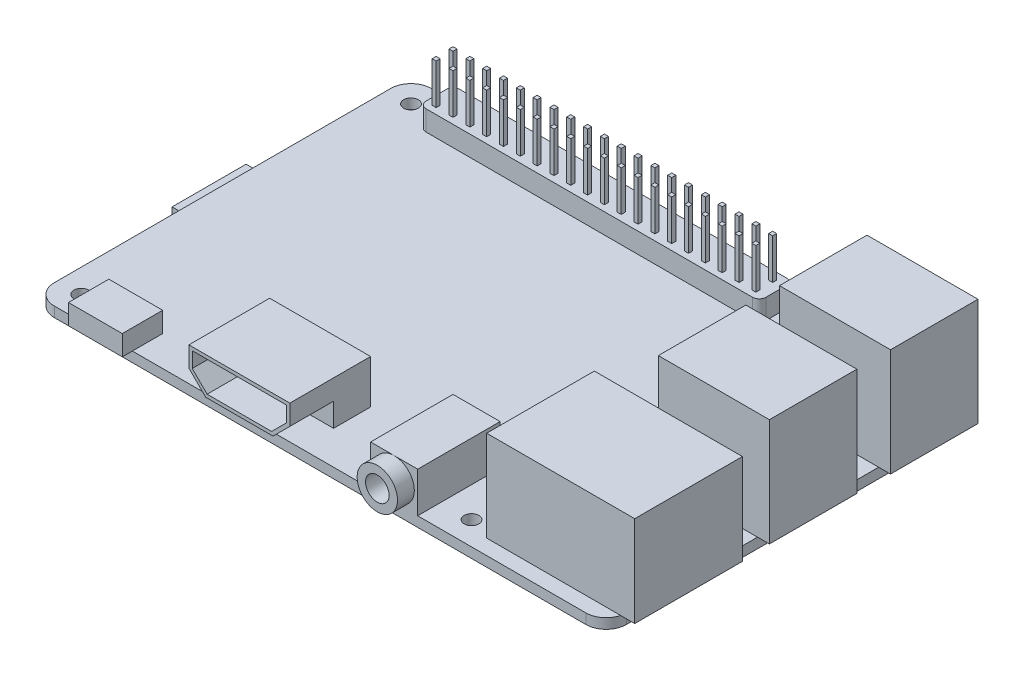
SolidWorks part; units mm, degrees
ref_plane "Front" through (0, 0, 0) normal (0, 0, 1) x (1, 0, 0)
ref_plane "Top" through (0, 0, 0) normal (0, 1, 0) x (1, 0, 0)
ref_plane "Right" through (0, 0, 0) normal (1, 0, 0) x (0, 0, -1)
sketch "Sketch1" plane through (0, 0, 0) normal (0, 1, 0) x (1, 0, 0)
  line L0 (-42.5, 28) -> (42.5, -28) construction
  line L1 (-42.5, 28) -> (42.5, 28)
  line L2 (-42.5, 28) -> (-42.5, -28)
  line L3 (-42.5, -28) -> (42.5, -28)
  line L4 (42.5, 28) -> (42.5, -28)
  line L5 (-42.5, -28) -> (42.5, 28) construction
  circle A0 centre (-39, 24.5) radius 2.6471
  circle A1 centre (-39, 24.5) radius 1.0947
  circle A2 centre (19, 24.5) radius 1.0947
  circle A3 centre (19, 24.5) radius 2.6471
  circle A4 centre (19, -24.5) radius 1.0947
  circle A5 centre (19, -24.5) radius 2.6471
  circle A6 centre (-39, -24.5) radius 1.0947
  circle A7 centre (-39, -24.5) radius 2.6471
  dimension "D1" = 85
  dimension "D2" = 56
  dimension "D3" = 3.5
  dimension "D4" = 3.5
  dimension "D5" = 2
  dimension "D6" = 2
extrude "Boss-Extrude1" add sketch "Sketch1" along normal blind 1.5 contours A0 A1 | A7 A6 | A5 A4 | L4 L1 L2 L3 A7 A5 A3 A0 | A3 A2
fillet "Fillet1" radius 3 4 edges at (42.5, 0.75, -28) (42.5, 0.75, 28) (-42.5, 0.75, 28) (-42.5, 0.75, -28)
sketch "Sketch2" plane through (0, 1.5, 0) normal (0, 1, 0) x (1, 0, 0)
  line L0 (-10.5, -29.5) -> (-10.5, -17.5) construction
  line L1 (-18, -17.5) -> (-3, -17.5)
  line L2 (-18, -17.5) -> (-18, -29.5)
  line L3 (-18, -29.5) -> (-3, -29.5)
  line L4 (-3, -17.5) -> (-3, -29.5)
  line L5 (-42.5, 25) -> (-42.5, -25) construction
  line L7 (-39.5, -28) -> (39.5, -28) construction
  dimension "D1" = 32
  dimension "D2" = 15
  dimension "D3" = 12
  dimension "D4" = 1.5
extrude "Boss-Extrude2" add sketch "Sketch2" along normal blind 6.5
sketch "Sketch3" plane through (0, 0, 29.5) normal (0, 0, 1) x (1, 0, 0)
  line L0 (-10.5, 7.5) -> (-3.5, 7.5)
  line L1 (-3.5, 7.5) -> (-3.5, 5.2071)
  line L2 (-3.5, 5.2071) -> (-5.7071, 3)
  line L3 (-5.7071, 3) -> (-10.5, 3)
  line L6 (-10.5, 8) -> (-3, 8)
  line L7 (-10.5, 8) -> (-10.5, 1.5) construction
  line L8 (-18, 8) -> (-3, 8) construction
  line L9 (-18, 1.5) -> (-3, 1.5) construction
  line L10 (-3, 8) -> (-3, 5)
  line L11 (-3, 5) -> (-5.5, 2.5)
  line L12 (-5.5, 2.5) -> (-10.5, 2.5)
  line L14 (-3, 8) -> (-3, 1.5) construction
  line L15 (-15.2929, 3) -> (-10.5, 3)
  line L16 (-15.5, 2.5) -> (-10.5, 2.5)
  line L17 (-18, 5) -> (-15.5, 2.5)
  line L18 (-17.5, 5.2071) -> (-15.2929, 3)
  line L19 (-17.5, 7.5) -> (-17.5, 5.2071)
  line L20 (-18, 8) -> (-18, 5)
  line L21 (-10.5, 8) -> (-18, 8)
  line L22 (-10.5, 7.5) -> (-17.5, 7.5)
  line M8 (-18, 1.5) -> (-3, 1.5)
  line M9 (-3, 1.5) -> (-3, 8)
  line M11 (-18, 8) -> (-18, 1.5)
  dimension "D1" = 7
  dimension "D3" = 1
  dimension "D4" = 5.5
  dimension "D5" = 2.5
  dimension "D6" = 45
  dimension "D2" = 0.5
extrude "Cut-Extrude1" cut sketch "Sketch3" against normal blind 6.5 contours L7 L22 L19 L18 L15 | L0 L7 L3 L2 L1 | L7 L16 L17 M11 M8 | L12 L7 L11 M8 M9
sketch "Sketch4" plane through (0, 1.5, 0) normal (0, 1, 0) x (1, 0, 0)
  line L0 (27.7652, 19) -> (44.2652, 19) construction
  line L1 (27.7652, 25.5) -> (44.2652, 25.5)
  line L2 (27.7652, 25.5) -> (27.7652, 12.5)
  line L3 (27.7652, 12.5) -> (44.2652, 12.5)
  line L4 (44.2652, 25.5) -> (44.2652, 12.5)
  line L5 (-39.5, -28) -> (39.5, -28) construction
  line L6 (27.7652, 7.5) -> (27.7652, -5.5)
  line L7 (27.7652, 7.5) -> (44.2652, 7.5)
  line L8 (44.2652, 7.5) -> (44.2652, -5.5)
  line L9 (27.7652, -5.5) -> (44.2652, -5.5)
  dimension "D1" = 47
  dimension "D2" = 16.5
  dimension "D3" = 13
  dimension "D4" = 2
extrude "Boss-Extrude3" add sketch "Sketch4" along normal blind 16
sketch "Sketch5" plane through (0, 1.5, 0) normal (0, 1, 0) x (1, 0, 0)
  line L0 (22.5, -17.75) -> (44.5, -17.75) construction
  line L1 (22.5, -9.75) -> (44.5, -9.75)
  line L2 (22.5, -9.75) -> (22.5, -25.75)
  line L3 (22.5, -25.75) -> (44.5, -25.75)
  line L4 (44.5, -9.75) -> (44.5, -25.75)
  line L5 (-39.5, -28) -> (39.5, -28) construction
  line L6 (42.5, -5.5) -> (42.5, -25) construction
  dimension "D1" = 10.25
  dimension "D2" = 22
  dimension "D3" = 16
  dimension "D4" = 2
extrude "Boss-Extrude4" add sketch "Sketch5" along normal blind 13.5
sketch "Sketch6" plane through (0, 1.5, 0) normal (0, 1, 0) x (1, 0, 0)
  line L0 (11, -15.75) -> (11, -30.5) construction
  line L1 (7.5, -15.75) -> (14.5, -15.75)
  line L2 (7.5, -15.75) -> (7.5, -30.5)
  line L3 (7.5, -30.5) -> (14.5, -30.5)
  line L4 (14.5, -15.75) -> (14.5, -30.5)
  line L5 (-42.5, 25) -> (-42.5, -25) construction
  line L6 (-39.5, -28) -> (39.5, -28) construction
  dimension "D1" = 14.75
  dimension "D2" = 7
  dimension "D3" = 53.5
  dimension "D4" = 2.5
extrude "Boss-Extrude5" add sketch "Sketch6" along normal blind 6
sketch "Sketch7" plane through (0, 0, 30.5) normal (0, 0, 1) x (1, 0, 0)
  line L0 (14.5, 4.5) -> (7.5, 4.5) construction
  line L1 (14.5, 7.5) -> (14.5, 1.5) construction
  line L2 (7.5, 7.5) -> (7.5, 1.5) construction
  circle A0 centre (11, 4.5) radius 3
  circle A1 centre (11, 4.5) radius 1.75
  line M3 (7.5, 1.5) -> (14.5, 1.5)
  line M4 (14.5, 1.5) -> (14.5, 7.5)
  line M5 (14.5, 7.5) -> (7.5, 7.5)
  line M6 (7.5, 7.5) -> (7.5, 1.5)
  dimension "D1" = 6
  dimension "D2" = 3.5
extrude "Cut-Extrude2" cut sketch "Sketch7" against normal blind 2.5 contours L0 A0 M5 M6 | L0 A0 M4 M5 | L0 A0 M4 M3 | A0 L0 M6 M3 | A1
sketch "Sketch8" plane through (0, 1.5, 0) normal (0, 1, 0) x (1, 0, 0)
  line L0 (-31.9, -29.5) -> (-31.9, -23.5) construction
  line L1 (-35.9, -23.5) -> (-27.9, -23.5)
  line L2 (-35.9, -23.5) -> (-35.9, -29.5)
  line L3 (-35.9, -29.5) -> (-27.9, -29.5)
  line L4 (-27.9, -23.5) -> (-27.9, -29.5)
  line L5 (-42.5, 25) -> (-42.5, -25) construction
  line L6 (-39.5, -28) -> (7.5, -28) construction
  dimension "D1" = 10.6
  dimension "D2" = 6
  dimension "D3" = 8
  dimension "D4" = 1.5
extrude "Boss-Extrude6" add sketch "Sketch8" along normal blind 3
sketch "Sketch9" plane through (0, 1.5, 0) normal (0, 1, 0) x (1, 0, 0)
  line L0 (-10, 27) -> (-10, 22) construction
  line L1 (-35.25, 27) -> (15.25, 27)
  line L2 (-35.25, 27) -> (-35.25, 22)
  line L3 (-35.25, 22) -> (15.25, 22)
  line L4 (15.25, 27) -> (15.25, 22)
  line L6 (-39, 24.5) -> (-10, 24.5) construction
  dimension "D1" = 29
  dimension "D2" = 5
  dimension "D3" = 50.5
extrude "Boss-Extrude7" add sketch "Sketch9" along normal blind 3
fillet "Fillet2" radius 1 4 edges at (-35.25, 3, -27) (15.25, 3, -27) (15.25, 3, -22) (-35.25, 3, -22)
sketch "Sketch10" plane through (0, 4.5, 0) normal (0, 1, 0) x (1, 0, 0)
  line L0 (-33.65, 25.7) -> (-35.25, 25.7) construction
  line L1 (-34.25, 25.4) -> (-33.65, 25.4)
  line L2 (-34.25, 25.4) -> (-34.25, 26)
  line L3 (-34.25, 26) -> (-33.65, 26)
  line L4 (-33.65, 25.4) -> (-33.65, 26)
  line L7 (-35.25, 26) -> (-35.25, 23) construction
  line L8 (-33.95, 26) -> (-33.95, 27) construction
  line L9 (14.25, 27) -> (-34.25, 27) construction
  line L10 (-31.75, 25.4) -> (-31.75, 26)
  line L11 (-31.75, 25.4) -> (-31.15, 25.4)
  line L12 (-31.15, 25.4) -> (-31.15, 26)
  line L13 (-31.75, 26) -> (-31.15, 26)
  line L14 (-29.25, 25.4) -> (-29.25, 26)
  line L15 (-29.25, 25.4) -> (-28.65, 25.4)
  line L16 (-28.65, 25.4) -> (-28.65, 26)
  line L17 (-29.25, 26) -> (-28.65, 26)
  line L18 (-26.75, 25.4) -> (-26.75, 26)
  line L19 (-26.75, 25.4) -> (-26.15, 25.4)
  line L20 (-26.15, 25.4) -> (-26.15, 26)
  line L21 (-26.75, 26) -> (-26.15, 26)
  line L22 (-24.25, 25.4) -> (-24.25, 26)
  line L23 (-24.25, 25.4) -> (-23.65, 25.4)
  line L24 (-23.65, 25.4) -> (-23.65, 26)
  line L25 (-24.25, 26) -> (-23.65, 26)
  line L26 (-21.75, 25.4) -> (-21.75, 26)
  line L27 (-21.75, 25.4) -> (-21.15, 25.4)
  line L28 (-21.15, 25.4) -> (-21.15, 26)
  line L29 (-21.75, 26) -> (-21.15, 26)
  line L30 (-19.25, 25.4) -> (-19.25, 26)
  line L31 (-19.25, 25.4) -> (-18.65, 25.4)
  line L32 (-18.65, 25.4) -> (-18.65, 26)
  line L33 (-19.25, 26) -> (-18.65, 26)
  line L34 (-16.75, 25.4) -> (-16.75, 26)
  line L35 (-16.75, 25.4) -> (-16.15, 25.4)
  line L36 (-16.15, 25.4) -> (-16.15, 26)
  line L37 (-16.75, 26) -> (-16.15, 26)
  line L38 (-14.25, 25.4) -> (-14.25, 26)
  line L39 (-14.25, 25.4) -> (-13.65, 25.4)
  line L40 (-13.65, 25.4) -> (-13.65, 26)
  line L41 (-14.25, 26) -> (-13.65, 26)
  line L42 (-11.75, 25.4) -> (-11.75, 26)
  line L43 (-11.75, 25.4) -> (-11.15, 25.4)
  line L44 (-11.15, 25.4) -> (-11.15, 26)
  line L45 (-11.75, 26) -> (-11.15, 26)
  line L46 (-9.25, 25.4) -> (-9.25, 26)
  line L47 (-9.25, 25.4) -> (-8.65, 25.4)
  line L48 (-8.65, 25.4) -> (-8.65, 26)
  line L49 (-9.25, 26) -> (-8.65, 26)
  line L50 (-6.75, 25.4) -> (-6.75, 26)
  line L51 (-6.75, 25.4) -> (-6.15, 25.4)
  line L52 (-6.15, 25.4) -> (-6.15, 26)
  line L53 (-6.75, 26) -> (-6.15, 26)
  line L54 (-4.25, 25.4) -> (-4.25, 26)
  line L55 (-4.25, 25.4) -> (-3.65, 25.4)
  line L56 (-3.65, 25.4) -> (-3.65, 26)
  line L57 (-4.25, 26) -> (-3.65, 26)
  line L58 (-1.75, 25.4) -> (-1.75, 26)
  line L59 (-1.75, 25.4) -> (-1.15, 25.4)
  line L60 (-1.15, 25.4) -> (-1.15, 26)
  line L61 (-1.75, 26) -> (-1.15, 26)
  line L62 (0.75, 25.4) -> (0.75, 26)
  line L63 (0.75, 25.4) -> (1.35, 25.4)
  line L64 (1.35, 25.4) -> (1.35, 26)
  line L65 (0.75, 26) -> (1.35, 26)
  line L66 (3.25, 25.4) -> (3.25, 26)
  line L67 (3.25, 25.4) -> (3.85, 25.4)
  line L68 (3.85, 25.4) -> (3.85, 26)
  line L69 (3.25, 26) -> (3.85, 26)
  line L70 (5.75, 25.4) -> (5.75, 26)
  line L71 (5.75, 25.4) -> (6.35, 25.4)
  line L72 (6.35, 25.4) -> (6.35, 26)
  line L73 (5.75, 26) -> (6.35, 26)
  line L74 (8.25, 25.4) -> (8.25, 26)
  line L75 (8.25, 25.4) -> (8.85, 25.4)
  line L76 (8.85, 25.4) -> (8.85, 26)
  line L77 (8.25, 26) -> (8.85, 26)
  line L78 (10.75, 25.4) -> (10.75, 26)
  line L79 (10.75, 25.4) -> (11.35, 25.4)
  line L80 (11.35, 25.4) -> (11.35, 26)
  line L81 (10.75, 26) -> (11.35, 26)
  line L82 (13.25, 25.4) -> (13.25, 26)
  line L83 (13.25, 25.4) -> (13.85, 25.4)
  line L84 (13.85, 25.4) -> (13.85, 26)
  line L85 (13.25, 26) -> (13.85, 26)
  line L86 (-31.75, 22.9) -> (-31.75, 23.5)
  line L87 (-31.75, 22.9) -> (-31.15, 22.9)
  line L88 (-31.15, 22.9) -> (-31.15, 23.5)
  line L89 (-31.75, 23.5) -> (-31.15, 23.5)
  line L90 (-29.25, 22.9) -> (-29.25, 23.5)
  line L91 (-29.25, 22.9) -> (-28.65, 22.9)
  line L92 (-28.65, 22.9) -> (-28.65, 23.5)
  line L93 (-29.25, 23.5) -> (-28.65, 23.5)
  line L94 (-26.75, 22.9) -> (-26.75, 23.5)
  line L95 (-26.75, 22.9) -> (-26.15, 22.9)
  line L96 (-26.15, 22.9) -> (-26.15, 23.5)
  line L97 (-26.75, 23.5) -> (-26.15, 23.5)
  line L98 (-24.25, 22.9) -> (-24.25, 23.5)
  line L99 (-24.25, 22.9) -> (-23.65, 22.9)
  line L100 (-23.65, 22.9) -> (-23.65, 23.5)
  line L101 (-24.25, 23.5) -> (-23.65, 23.5)
  line L102 (-21.75, 22.9) -> (-21.75, 23.5)
  line L103 (-21.75, 22.9) -> (-21.15, 22.9)
  line L104 (-21.15, 22.9) -> (-21.15, 23.5)
  line L105 (-21.75, 23.5) -> (-21.15, 23.5)
  line L106 (-19.25, 22.9) -> (-19.25, 23.5)
  line L107 (-19.25, 22.9) -> (-18.65, 22.9)
  line L108 (-18.65, 22.9) -> (-18.65, 23.5)
  line L109 (-19.25, 23.5) -> (-18.65, 23.5)
  line L110 (-16.75, 22.9) -> (-16.75, 23.5)
  line L111 (-16.75, 22.9) -> (-16.15, 22.9)
  line L112 (-16.15, 22.9) -> (-16.15, 23.5)
  line L113 (-16.75, 23.5) -> (-16.15, 23.5)
  line L114 (-14.25, 22.9) -> (-14.25, 23.5)
  line L115 (-14.25, 22.9) -> (-13.65, 22.9)
  line L116 (-13.65, 22.9) -> (-13.65, 23.5)
  line L117 (-14.25, 23.5) -> (-13.65, 23.5)
  line L118 (-11.75, 22.9) -> (-11.75, 23.5)
  line L119 (-11.75, 22.9) -> (-11.15, 22.9)
  line L120 (-11.15, 22.9) -> (-11.15, 23.5)
  line L121 (-11.75, 23.5) -> (-11.15, 23.5)
  line L122 (-9.25, 22.9) -> (-9.25, 23.5)
  line L123 (-9.25, 22.9) -> (-8.65, 22.9)
  line L124 (-8.65, 22.9) -> (-8.65, 23.5)
  line L125 (-9.25, 23.5) -> (-8.65, 23.5)
  line L126 (-6.75, 22.9) -> (-6.75, 23.5)
  line L127 (-6.75, 22.9) -> (-6.15, 22.9)
  line L128 (-6.15, 22.9) -> (-6.15, 23.5)
  line L129 (-6.75, 23.5) -> (-6.15, 23.5)
  line L130 (-4.25, 22.9) -> (-4.25, 23.5)
  line L131 (-4.25, 22.9) -> (-3.65, 22.9)
  line L132 (-3.65, 22.9) -> (-3.65, 23.5)
  line L133 (-4.25, 23.5) -> (-3.65, 23.5)
  line L134 (-1.75, 22.9) -> (-1.75, 23.5)
  line L135 (-1.75, 22.9) -> (-1.15, 22.9)
  line L136 (-1.15, 22.9) -> (-1.15, 23.5)
  line L137 (-1.75, 23.5) -> (-1.15, 23.5)
  line L138 (0.75, 22.9) -> (0.75, 23.5)
  line L139 (0.75, 22.9) -> (1.35, 22.9)
  line L140 (1.35, 22.9) -> (1.35, 23.5)
  line L141 (0.75, 23.5) -> (1.35, 23.5)
  line L142 (3.25, 22.9) -> (3.25, 23.5)
  line L143 (3.25, 22.9) -> (3.85, 22.9)
  line L144 (3.85, 22.9) -> (3.85, 23.5)
  line L145 (3.25, 23.5) -> (3.85, 23.5)
  line L146 (5.75, 22.9) -> (5.75, 23.5)
  line L147 (5.75, 22.9) -> (6.35, 22.9)
  line L148 (6.35, 22.9) -> (6.35, 23.5)
  line L149 (5.75, 23.5) -> (6.35, 23.5)
  line L150 (8.25, 22.9) -> (8.25, 23.5)
  line L151 (8.25, 22.9) -> (8.85, 22.9)
  line L152 (8.85, 22.9) -> (8.85, 23.5)
  line L153 (8.25, 23.5) -> (8.85, 23.5)
  line L154 (10.75, 22.9) -> (10.75, 23.5)
  line L155 (10.75, 22.9) -> (11.35, 22.9)
  line L156 (11.35, 22.9) -> (11.35, 23.5)
  line L157 (10.75, 23.5) -> (11.35, 23.5)
  line L158 (13.25, 22.9) -> (13.25, 23.5)
  line L159 (13.25, 22.9) -> (13.85, 22.9)
  line L160 (13.85, 22.9) -> (13.85, 23.5)
  line L161 (13.25, 23.5) -> (13.85, 23.5)
  line L162 (-34.25, 22.9) -> (-34.25, 23.5)
  line L163 (-34.25, 22.9) -> (-33.65, 22.9)
  line L164 (-33.65, 22.9) -> (-33.65, 23.5)
  line L165 (-34.25, 23.5) -> (-33.65, 23.5)
  dimension "D1" = 1
  dimension "D2" = 1.6
  dimension "D3" = 0.6
  dimension "D4" = 20
  dimension "D5" = 2
extrude "Boss-Extrude8" add sketch "Sketch10" along normal blind 6
sketch "Sketch11" plane through (0, 0, 0) normal (0, -1, 0) x (1, 0, 0)
  line L1 (-45, 5) -> (-29.5, 5)
  line L2 (-45, 5) -> (-45, -6)
  line L3 (-45, -6) -> (-29.5, -6)
  line L4 (-29.5, 5) -> (-29.5, -6)
  line L5 (-39.5, -28) -> (39.5, -28) construction
  line L6 (-42.5, -25) -> (-42.5, 25) construction
  dimension "D1" = 33
  dimension "D2" = 11
  dimension "D3" = 2.5
  dimension "D4" = 15.5
extrude "Boss-Extrude9" add sketch "Sketch11" along normal blind 1.5
equation "\"D4@Sketch1\"=\"D3@Sketch1\""
equation "\"2mmm\"=7.49637"
